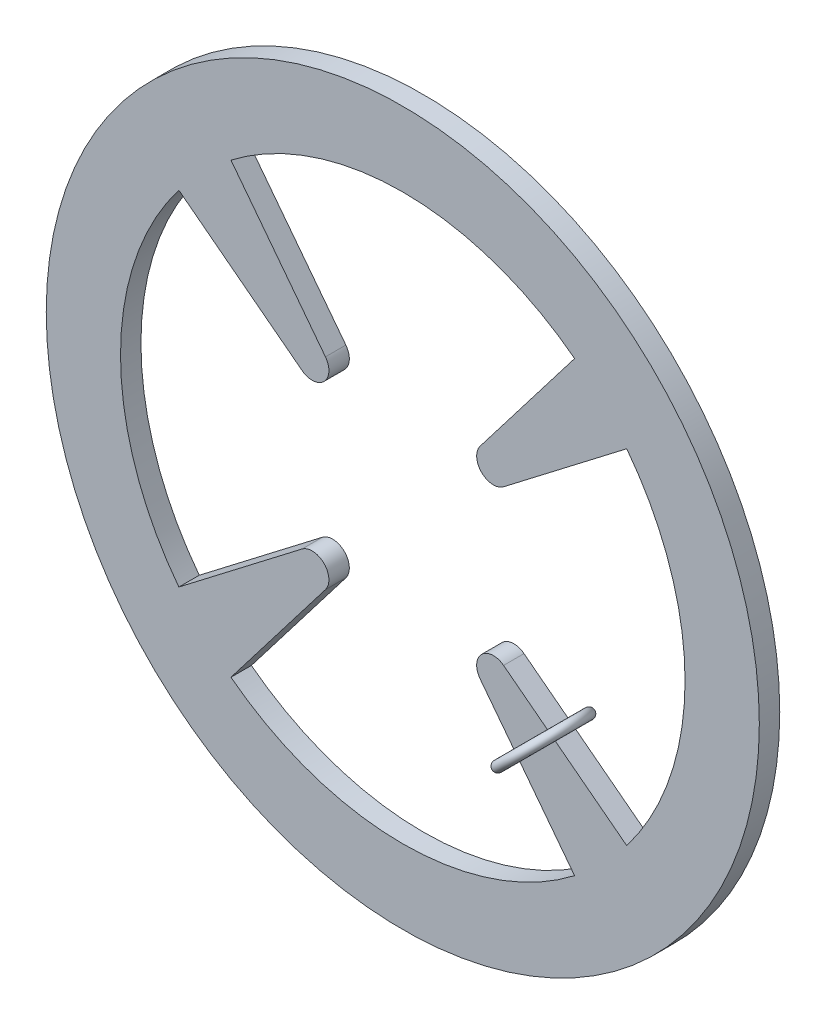
SolidWorks part; units mm, degrees
other "標示1"
sketch "草圖65"
ref_plane "前基準面" through (0, 0, 0) normal (0, 0, 1) x (1, 0, 0)
ref_plane "上基準面" through (0, 0, 0) normal (0, 1, 0) x (1, 0, 0)
ref_plane "右基準面" through (0, 0, 0) normal (1, 0, 0) x (0, 0, -1)
sketch "草圖1" plane through (0, 0, 0) normal (0, 0, 1) x (1, 0, 0)
  circle A0 centre (0, 0) radius 0.96
  circle A1 centre (0, 0) radius 0.76
extrude "填料-伸長1" add sketch "草圖1" along normal blind 0.055
sketch "草圖2" plane through (0, 0, 0.055) normal (0, 0, 1) x (1, 0, 0)
  line L0 (0, 0) -> (0, 1.565) construction
  line L1 (0, 0) -> (-1.8584, 0) construction
  line L2 (-0.0447, 0.3392) -> (-0.0992, 0.7535)
  line L3 (0.0447, 0.3392) -> (0.0992, 0.7535)
  line L4 (0.2714, 0.2082) -> (0.6029, 0.4627)
  line L5 (0.2082, 0.2714) -> (0.4627, 0.6029)
  line L6 (0.2082, -0.2714) -> (0.4627, -0.6029)
  line L7 (0.2714, -0.2082) -> (0.6029, -0.4627)
  line L8 (-0.2714, -0.2082) -> (-0.6029, -0.4627)
  line L9 (-0.2082, -0.2714) -> (-0.4627, -0.6029)
  line L10 (-0.2082, 0.2714) -> (-0.4627, 0.6029)
  line L11 (-0.2714, 0.2082) -> (-0.6029, 0.4627)
  circle A0 centre (0, 0) radius 0.3
  circle A1 centre (0, 0) radius 0.76 construction
  arc A3 (-0.0447, 0.3392) -> (0.0447, 0.3392) centre (0, 0.345) ccw
  arc A4 (0.0992, 0.7535) -> (-0.0992, 0.7535) centre (0, 0) ccw
  arc A5 (-0.76, 0) -> (0.76, 0) centre (0, 0) ccw
  arc A6 (0.6029, 0.4627) -> (0.4627, 0.6029) centre (0, 0) ccw
  arc A7 (0.2082, 0.2714) -> (0.2714, 0.2082) centre (0.244, 0.244) ccw
  arc A8 (0.4627, -0.6029) -> (0.6029, -0.4627) centre (0, 0) ccw
  arc A9 (0.2714, -0.2082) -> (0.2082, -0.2714) centre (0.244, -0.244) ccw
  arc A10 (-0.6029, -0.4627) -> (-0.4627, -0.6029) centre (0, 0) ccw
  arc A11 (-0.2082, -0.2714) -> (-0.2714, -0.2082) centre (-0.244, -0.244) ccw
  arc A12 (-0.4627, 0.6029) -> (-0.6029, 0.4627) centre (0, 0) ccw
  arc A13 (-0.2714, 0.2082) -> (-0.2082, 0.2714) centre (-0.244, 0.244) ccw
  point P23 (0, 0)
  point P34 (0, 0)
  point P41 (0, 0)
  circle M4 centre (0, 0) radius 0.76
  dimension "D1" = 7.5
  dimension "D3" = 2
  dimension "D4" = 4
  dimension "D2" = 7.5
extrude "填料-伸長2" add sketch "草圖2" against normal blind 0.055 contours L11 A13 L10 M4 | L5 A7 L4 M4 | L7 A9 L6 M4 | A11 L8 L9 M4
sketch "草圖7" plane through (0, 0, 0.055) normal (0, 0, 1) x (1, 0, 0)
  line L0 (0.2121, 0.2121) -> (0.2404, 0.2404) construction
  line L1 (0.2404, 0.2404) -> (0.2013, 0.2795) construction
  line L2 (0.2404, 0.2404) -> (0.5894, 0.5894) construction
  line L3 (0.0244, -0.0244) -> (-0.6648, 0.6648) construction
  line L4 (0.2404, -0.2404) -> (0.3328, -0.148)
  arc A0 (0.2082, 0.2714) -> (0.2714, 0.2082) centre (0.244, 0.244) ccw construction
  arc A1 (-0.2082, -0.2714) -> (-0.2714, -0.2082) centre (-0.244, -0.244) ccw construction
  arc A2 (-0.2714, 0.2082) -> (-0.2082, 0.2714) centre (-0.244, 0.244) ccw construction
  arc A3 (0.2714, -0.2082) -> (0.2082, -0.2714) centre (0.244, -0.244) ccw construction
  point P5 (0.297, 0.297)
  point P7 (-0.2121, -0.2121)
  point P8 (0.3536, 0.3536)
  point P9 (0.4101, 0.4101)
  point P12 (-0.2404, -0.2404)
  point P16 (-0.297, -0.297)
  point P17 (-0.3536, -0.3536)
  point P18 (-0.4101, -0.4101)
  point P20 (0.2404, -0.2404)
  point P21 (0, 0)
  point P23 (-0.2404, 0.2404)
  point P24 (-0.2121, 0.2121)
  point P25 (0.2121, -0.2121)
  point P29 (0.297, -0.297)
  point P33 (0.3536, -0.3536)
  point P34 (0.4101, -0.4101)
  point P35 (-0.297, 0.297)
  point P36 (-0.3536, 0.3536)
  point P37 (-0.4101, 0.4101)
  point P40 (0.4667, -0.4667)
  point P41 (0.5233, -0.5233)
  point P42 (0.4667, 0.4667)
  point P43 (0.5233, 0.5233)
  point P44 (-0.4667, 0.4667)
  point P45 (-0.5233, 0.5233)
  point P46 (-0.4667, -0.4667)
  point P47 (-0.5233, -0.5233)
  dimension "D1" = 0.08
  dimension "D2" = 0.08
  dimension "D3" = 0.08
  dimension "D4" = 0.04
  dimension "D5" = 0.04
  dimension "D6" = 0.08
  dimension "D7" = 0.08
  dimension "D8" = 0.08
  dimension "D9" = 0.04
  dimension "D10" = 0.04
  dimension "D11" = 0.08
  dimension "D12" = 0.08
  dimension "D13" = 0.08
  dimension "D14" = 0.08
  dimension "D15" = 0.08
  dimension "D16" = 0.08
  dimension "D17" = 0.08
  dimension "D18" = 0.08
  dimension "D19" = 0.08
  dimension "D20" = 0.08
  dimension "D21" = 0.08
  dimension "D22" = 0.08
  dimension "D23" = 0.08
  dimension "D24" = 0.08
ref_plane "平面5" through (0.2404, 0.2404, 0) normal (0.7071, 0.7071, 0) x (-0.7071, 0.7071, 0)
ref_plane "平面6" through (0.297, 0.297, 0) normal (0.7071, 0.7071, 0) x (0.7071, -0.7071, 0)
ref_plane "平面7" through (0.3536, 0.3536, 0) normal (0.7071, 0.7071, 0) x (0.7071, -0.7071, 0)
ref_plane "平面8" through (0.4101, 0.4101, 0) normal (0.7071, 0.7071, 0) x (0.7071, -0.7071, 0)
ref_plane "平面9" through (-0.2404, -0.2404, 0) normal (0.7071, 0.7071, 0) x (0.7071, -0.7071, 0)
ref_plane "平面10" through (-0.297, -0.297, 0) normal (0.7071, 0.7071, 0) x (0.7071, -0.7071, 0)
ref_plane "平面11" through (-0.3536, -0.3536, 0) normal (0.7071, 0.7071, 0) x (0.7071, -0.7071, 0)
ref_plane "平面12" through (-0.4101, -0.4101, 0) normal (0.7071, 0.7071, 0) x (0.7071, -0.7071, 0)
ref_plane "平面13" through (0.2404, -0.2404, 0) normal (0.7071, -0.7071, 0) x (0.7071, 0.7071, 0)
ref_plane "平面14" through (0.297, -0.297, 0) normal (0.7071, -0.7071, 0) x (0, 0, -1)
ref_plane "平面15" through (0.3536, -0.3536, 0) normal (0.7071, -0.7071, 0) x (0, 0, -1)
ref_plane "平面16" through (0.4101, -0.4101, 0) normal (0.7071, -0.7071, 0) x (0, 0, -1)
ref_plane "平面17" through (-0.2404, 0.2404, 0) normal (0.7071, -0.7071, 0) x (0, 0, -1)
ref_plane "平面18" through (-0.297, 0.297, 0) normal (0.7071, -0.7071, 0) x (0, 0, -1)
ref_plane "平面19" through (-0.3536, 0.3536, 0) normal (0.7071, -0.7071, 0) x (0, 0, -1)
ref_plane "平面20" through (-0.4101, 0.4101, 0) normal (0.7071, -0.7071, 0) x (0, 0, -1)
ref_plane "平面21" through (0, 0, 0) normal (-0.7071, -0.7071, 0) x (-0.7071, 0.7071, 0)
sketch "草圖68" plane through (0, 0, 0) normal (-0.7071, -0.7071, 0) x (-0.7071, 0.7071, 0)
  line L0 (-0.34, -0.0851) -> (-0.34, -0.3432)
  line L1 (-200000.0345, -0.055) -> (200000.9402, -0.055) construction
  circle A0 centre (-0.34, 0.025) radius 0.023
  point P1 (-0.34, 0.025)
  dimension "D1" = 0.08
sketch "草圖72" plane through (0.3536, -0.3536, 0) normal (0.7071, -0.7071, 0) x (0, 0, -1)
  line L0 (199999.9149, 0) -> (-200000.3432, 0) construction
  line L1 (-0.03, 0) -> (-0.03, 0.1)
  circle A0 centre (-0.03, 0) radius 0.1
  point P0 (-0.03, 0)
  point P8 (-0.03, 0.1)
  dimension "D1" = 0.025
ref_plane "平面24" through (0.4243, -0.2828, 0.03) normal (0, 0, 1) x (1, 0, 0)
sketch "草圖73" plane through (0.4243, -0.2828, 0.03) normal (0, 0, 1) x (1, 0, 0)
  circle A0 centre (0, 0) radius 0.0132
sweep "掃出2" add profiles "草圖73" path "草圖72"
